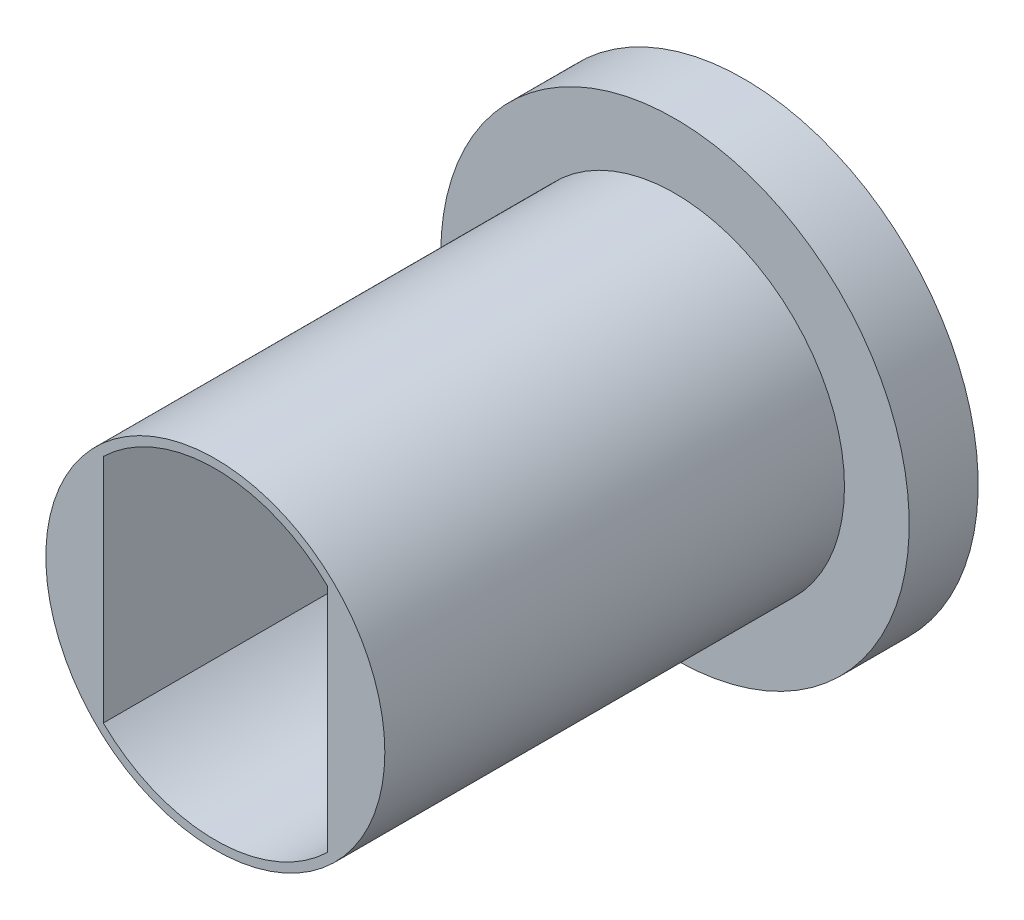
SolidWorks part; units mm, degrees
ref_plane "Plano frontal" through (0, 0, 0) normal (0, 0, 1) x (1, 0, 0)
ref_plane "Plano superior" through (0, 0, 0) normal (0, 1, 0) x (1, 0, 0)
ref_plane "Plano direito" through (0, 0, 0) normal (1, 0, 0) x (0, 0, -1)
sketch "Esboço1" plane through (0, 0, 0) normal (0, 0, 1) x (1, 0, 0)
  line L0 (1.85, 1.9666) -> (1.85, -1.9666) construction
  line L1 (-1.85, -1.9666) -> (-1.85, 1.9666) construction
  arc A0 (-1.85, -1.9666) -> (1.85, -1.9666) centre (0, 0) ccw construction
  arc A1 (1.85, 1.9666) -> (-1.85, 1.9666) centre (0, 0) ccw construction
  circle A2 centre (0, 0) radius 3.05 construction
sketch "Esboço2" plane through (0, 0, 0) normal (0, 0, 1) x (1, 0, 0)
  line L4 (1.95, -2.0094) -> (1.95, 2.0094)
  line L5 (-1.95, 2.0094) -> (-1.95, -2.0094)
  line L6 (1.95, -2.0094) -> (1.95, 2.0094)
  line L7 (-1.95, 2.0094) -> (-1.95, -2.0094)
  arc A7 (-1.95, -2.0094) -> (1.95, -2.0094) centre (0, 0) ccw
  arc A8 (1.95, 2.0094) -> (-1.95, 2.0094) centre (0, 0) ccw
  arc A9 (-1.95, -2.0094) -> (1.95, -2.0094) centre (0, 0) ccw
  arc A10 (1.95, 2.0094) -> (-1.95, 2.0094) centre (0, 0) ccw
  circle A12 centre (0, 0) radius 2.95
  circle A13 centre (0, 0) radius 2.95
  dimension "D1" = 0.1
  dimension "D2" = 0.1
extrude "Ressalto-extrusão1" add sketch "Esboço2" along normal blind 8
sketch "Esboço3" plane through (0, 0, 0) normal (0, 0, -1) x (-1, 0, 0)
  circle A0 centre (0, 0) radius 4.0766
  circle A5 centre (0, 0) radius 1.475
  circle A6 centre (0, 0) radius 0.975 construction
  dimension "D1" = 1.95
  dimension "D2" = 0.5
extrude "Ressalto-extrusão2" add sketch "Esboço3" along normal blind 1.2
